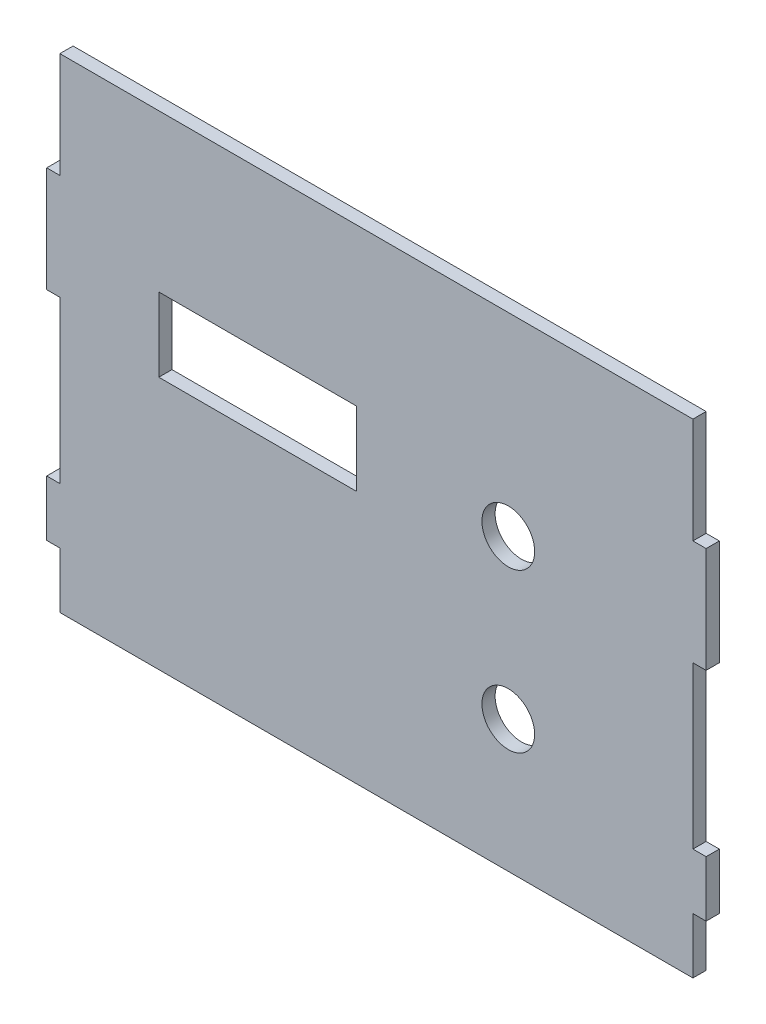
SolidWorks part; units mm, degrees
material "Contreplaqué pin"
ref_plane "Plan de face" through (0, 0, 0) normal (0, 0, 1) x (1, 0, 0)
ref_plane "Plan de dessus" through (0, 0, 0) normal (0, 1, 0) x (1, 0, 0)
ref_plane "Plan de droite" through (0, 0, 0) normal (1, 0, 0) x (0, 0, -1)
sketch "Esquisse1" plane through (0, 0, 0) normal (0, 0, 1) x (1, 0, 0)
  line L0 (0, 143.5) -> (0, 183.5)
  line L1 (0, 0) -> (240, 0)
  line L2 (0, 0) -> (0, 21.1667)
  line L3 (0, 183.5) -> (240, 183.5)
  line L4 (240, 0) -> (240, 21.1667)
  line L5 (0, 42.3333) -> (-5, 42.3333)
  line L7 (0, 21.1667) -> (-5, 21.1667)
  line L8 (-5, 42.3333) -> (-5, 21.1667)
  line L9 (0, 143.5) -> (-5, 143.5)
  line L11 (0, 103.5) -> (-5, 103.5)
  line L12 (-5, 143.5) -> (-5, 103.5)
  line L13 (240, 143.5) -> (245, 143.5)
  line L15 (240, 103.5) -> (245, 103.5)
  line L16 (245, 143.5) -> (245, 103.5)
  line L17 (240, 42.3333) -> (245, 42.3333)
  line L19 (240, 21.1667) -> (245, 21.1667)
  line L20 (245, 42.3333) -> (245, 21.1667)
  line L21 (0, 42.3333) -> (0, 103.5)
  line L22 (240, 42.3333) -> (240, 103.5)
  line L23 (240, 143.5) -> (240, 183.5)
  line L24 (0, 63.5) -> (240, 63.5) construction
  line L26 (37.5, 124) -> (112.5, 124)
  line L27 (37.5, 124) -> (37.5, 96)
  line L28 (37.5, 96) -> (112.5, 96)
  line L29 (112.5, 124) -> (112.5, 96)
  circle A0 centre (170, 110) radius 10
  circle A1 centre (170, 50) radius 10
  point P32 (37.5, 110)
  point P34 (75, 96)
  point P36 (112.5, 110)
  dimension "D11" = 20
  dimension "D1" = 183.5
  dimension "D2" = 240
  dimension "D3" = 5
  dimension "D4" = 5
  dimension "D5" = 120
  dimension "D6" = 40
  dimension "D7" = 40
  dimension "D8" = 63.5
  dimension "D9" = 21.1667
  dimension "D10" = 21.1667
  dimension "D12" = 170
  dimension "D13" = 60
  dimension "D14" = 110
  dimension "D15" = 75
  dimension "D16" = 75
  dimension "D17" = 28
extrude "Boss.-Extru.1" add sketch "Esquisse1" along normal blind 5
equation "\"D6@Esquisse1\"=\"D5@Esquisse1\"/3"
equation "\"D7@Esquisse1\"=\"D6@Esquisse1\""
equation "\"D9@Esquisse1\"=\"D8@Esquisse1\"/3"
equation "\"D10@Esquisse1\"=\"D9@Esquisse1\""
